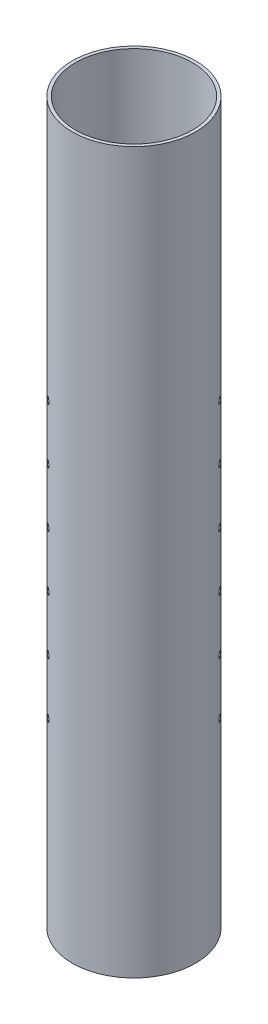
SolidWorks part; units mm, degrees
material "S-Glass Fiber"
ref_plane "Front Plane" through (0, 0, 0) normal (0, 0, 1) x (1, 0, 0)
ref_plane "Top Plane" through (0, 0, 0) normal (0, 1, 0) x (1, 0, 0)
ref_plane "Right Plane" through (0, 0, 0) normal (1, 0, 0) x (0, 0, -1)
ref_axis "ROCKET AXIS" through (0, 255, 0) along (0, -1, 0)
sketch "Sketch1" plane through (0, 0, 0) normal (0, 1, 0) x (1, 0, 0)
  circle A0 centre (0, 0) radius 32.5
  circle A1 centre (0, 0) radius 34.25
  dimension "D1" = 65
  dimension "D2" = 68.5
extrude "BULK" add sketch "Sketch1" along normal blind 400
ref_plane "AVIONICS FRONT SCREW HOLE PLANE" through (0, 0, 0) normal (-0.7071, 0, -0.7071) x (-0.7071, 0, 0.7071)
sketch "Sketch3" plane through (0, 0, 0) normal (-0.7071, 0, -0.7071) x (-0.7071, 0, 0.7071)
  circle A0 centre (0, 105) radius 1.75
  circle A1 centre (0, 135.6) radius 1.75
  circle A2 centre (0, 166.2) radius 1.75
  circle A3 centre (0, 196.8) radius 1.75
  circle A4 centre (0, 227.4) radius 1.75
  circle A5 centre (0, 258) radius 1.75
  dimension "D2" = 3.5
  dimension "D1" = 105
  dimension "D3" = 6
  dimension "D4" = 30.6
extrude "AVIONICS FRONT SCREW HOLES" cut sketch "Sketch3" along normal through all
pattern_circular "AVIONICS LEFT AND RIGHT SCREW HOLES" count 2 every 100 about axis through (0, 255, 0) along (0, -1, 0) of "AVIONICS FRONT SCREW HOLES"
ref_plane "UMBILICAL CONNECTOR MIDPLANE" through (0, 0, 0) normal (0.6088, 0, -0.7934) x (0, -1, 0)
sketch "Sketch4" plane through (0, 0, 0) normal (0.6088, 0, -0.7934) x (0, -1, 0)
  line L1 (-178.98, 35) -> (-138.98, 35)
  line L2 (-178.98, 35) -> (-178.98, 30)
  line L3 (-178.98, 30) -> (-138.98, 30)
  line L4 (-138.98, 35) -> (-138.98, 30)
  dimension "D1" = 12.78
  dimension "D2" = 40
  dimension "D3" = 35
  dimension "D4" = 30
revolve "UMBILICAL PASSTHRU CUT" cut sketch "Sketch4" angle 20 about axis through (0, 255, 0) along (0, -1, 0)
fillet "UMBILICAL PASSTHRU CORNER ROUNDING" radius 3 4 edges at (-26.4782, 178.98, -20.3174) (-31.8303, 178.98, -10.0361) (-31.8303, 138.98, -10.0361) (-26.4782, 138.98, -20.3174)
ref_plane "RBF CUTOUT MIDPLANE" through (0, 0, 0) normal (0.8936, 0, -0.4489) x (0, -1, 0)
ref_plane "RBF CUTOUT TANGENT PLANE" through (-15.3745, 0, -30.6053) normal (-0.4489, 0, -0.8936) x (-0.8936, 0, 0.4489)
sketch "Sketch5" plane through (-15.3745, 0, -30.6053) normal (-0.4489, 0, -0.8936) x (-0.8936, 0, 0.4489)
  line L1 (0, 60.5) -> (0, -60.5) construction
  circle A0 centre (0, 157.7) radius 5
  circle A1 centre (0, 172.9) radius 5
  dimension "D2" = 10
  dimension "D1" = 52.7
  dimension "D3" = 15.2
extrude "RBF CUTOUT" cut sketch "Sketch5" against normal up to next
